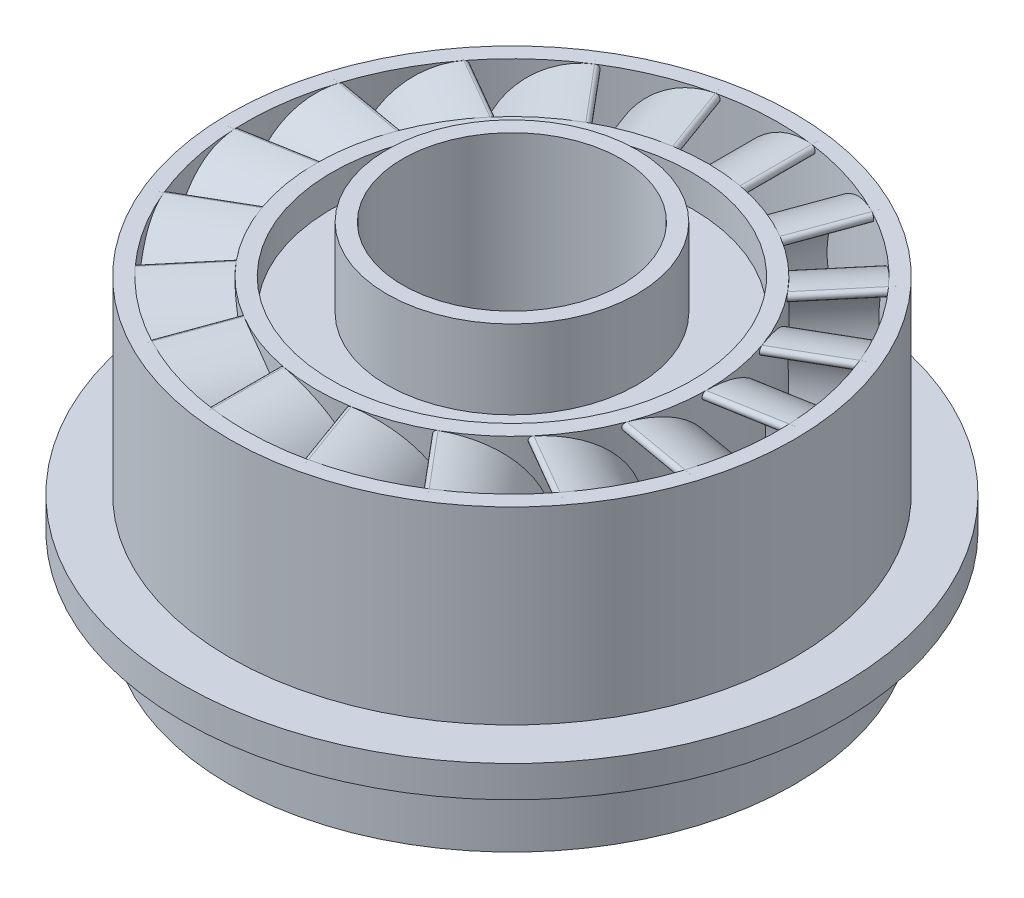
SolidWorks part; units mm, degrees
ref_plane "Ön Düzlem" through (0, 0, 0) normal (0, 0, 1) x (1, 0, 0)
ref_plane "Üst Düzlem" through (0, 0, 0) normal (0, 1, 0) x (1, 0, 0)
ref_plane "Sağ Düzlem" through (0, 0, 0) normal (1, 0, 0) x (0, 0, -1)
sketch "Çizim1" plane through (0, 0, 0) normal (0, 0, 1) x (1, 0, 0)
  line L0 (0, 0) -> (0, 16.742) construction
  line L1 (-24.9, 0) -> (-24.9, 14)
  line L2 (-24.9, 14) -> (-22.9, 14)
  line L3 (-22.9, 14) -> (-22.9, 10)
  line L4 (-22.9, 10) -> (-15.9, 10)
  line L5 (-15.9, 10) -> (-15.9, 20)
  line L6 (-15.9, 20) -> (-13.9, 20)
  line L7 (-13.9, 20) -> (-13.9, 0)
  line L8 (-13.9, 0) -> (-15.9, 0)
  line L9 (-15.9, 0) -> (-15.9, 5)
  line L10 (-15.9, 5) -> (-22.9, 5)
  line L11 (-22.9, 5) -> (-22.9, 0)
  line L12 (-22.9, 0) -> (-24.9, 0)
  dimension "D1" = 13.9
  dimension "D2" = 2
  dimension "D3" = 2
  dimension "D4" = 2
  dimension "D5" = 5
  dimension "D6" = 5
  dimension "D7" = 4
  dimension "D8" = 5
  dimension "D9" = 10
  dimension "D10" = 20
  dimension "D11" = 11
revolve "Döndür1" add sketch "Çizim1" angle 360 about L0
ref_plane "Düzlem1" through (0, 0, 24) normal (0, 0, 1) x (1, 0, 0)
sketch "Çizim2" plane through (0, 0, 24) normal (0, 0, 1) x (1, 0, 0)
  line L0 (0, 0) -> (0, 27.6876) construction
  line L1 (24.9, 14) -> (-24.9, 14) construction
  line L2 (-24.9, 0) -> (24.9, 0) construction
  line L3 (-24.9, 7) -> (31.7485, 7) construction
  line L4 (-24.9, 14) -> (-24.9, 0) construction
  arc A1 (-4.5315, 13) -> (4.4625, 0.65) centre (-4.5998, 3.5003) cw
  arc A2 (-4.5243, 14) -> (5.4165, 0.35) centre (-4.5998, 3.5003) cw
  arc A3 (-4.5243, 14) -> (-4.5315, 13) centre (-4.5279, 13.5) ccw
  arc A4 (4.4625, 0.65) -> (5.4165, 0.35) centre (4.9395, 0.5) ccw
extrude "Yükseklik-Ekstrüzyon2" add sketch "Çizim2" along normal blind 10.4
pattern_circular "Dairesel Kaplama1" count 18 over 360 about axis through (0, 0, 0) along (0, 1, 0) of "Yükseklik-Ekstrüzyon2"
sketch "Çizim3" plane through (0, 0, 0) normal (1, 0, 0) x (0, 0, -1)
  line L0 (0, 31.3682) -> (0, -16.7279) construction
  line L1 (33.9, 14) -> (33.9, -24)
  line L2 (34.4, 14) -> (24.4855, 14) construction
  line L3 (35.9, 14) -> (35.9, -10)
  line L4 (33.9, 14) -> (35.9, 14)
  line L5 (35.9, -24) -> (33.9, -24)
  line L6 (35.9, -14) -> (41.9, -14)
  line L7 (41.9, -14) -> (41.9, -10)
  line L8 (41.9, -10) -> (35.9, -10)
  line L9 (35.9, -14) -> (35.9, -24)
  line L10 (35.9, 14) -> (35.9, -24) construction
  dimension "D1" = 38
  dimension "D2" = 33.9
  dimension "D4" = 4
  dimension "D5" = 6
  dimension "D6" = 14
  dimension "D3" = 2
revolve "Döndür2" add sketch "Çizim3" angle 360 about L0
